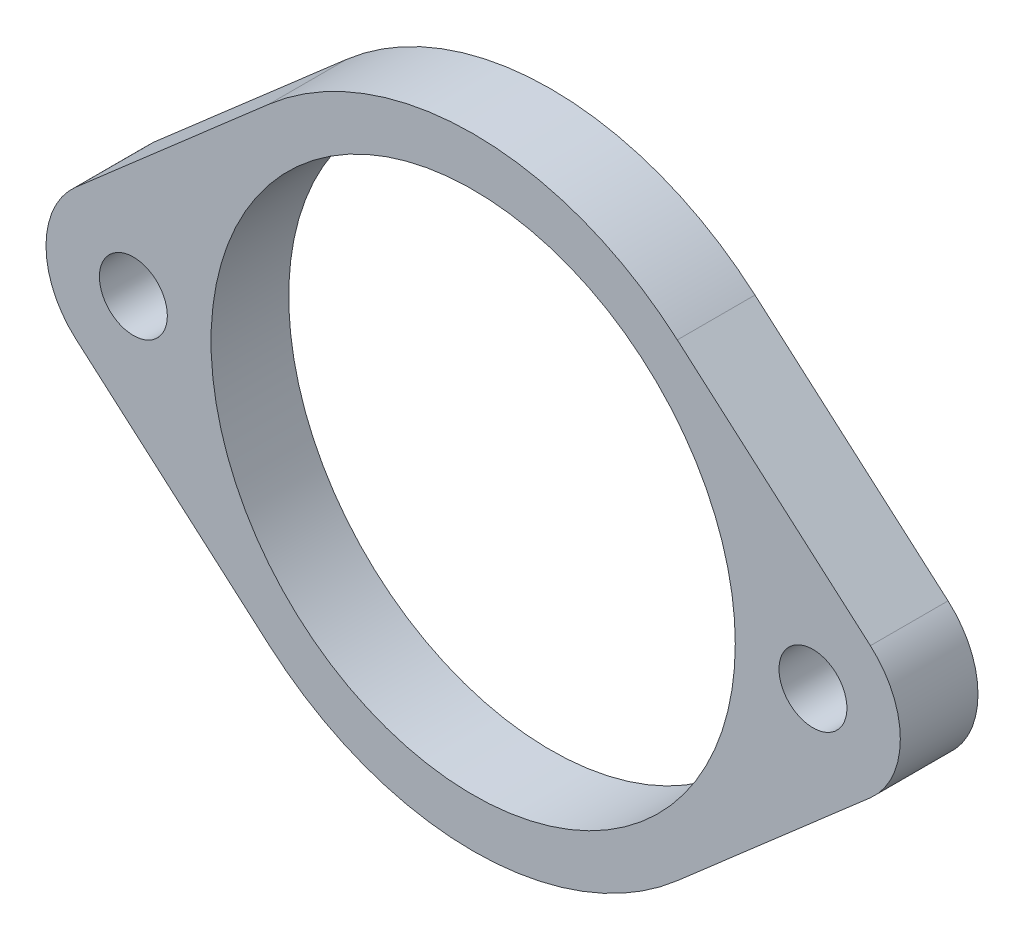
SolidWorks part; units mm, degrees
ref_plane "Front Plane" through (0, 0, 0) normal (0, 0, 1) x (1, 0, 0)
ref_plane "Top Plane" through (0, 0, 0) normal (0, 1, 0) x (1, 0, 0)
ref_plane "Right Plane" through (0, 0, 0) normal (1, 0, 0) x (0, 0, -1)
sketch "Sketch1" plane through (0, 0, 0) normal (0, 0, 1) x (1, 0, 0)
  line L4 (-16.6914, 19.1457) -> (-32.4757, 5.3847)
  line L5 (-32.4757, -5.3847) -> (-16.6914, -19.1457)
  line L6 (16.6914, -19.1457) -> (32.4757, -5.3847)
  line L7 (32.4757, 5.3847) -> (16.6914, 19.1457)
  line L8 (-16.6914, 19.1457) -> (-32.4757, 5.3847)
  line L9 (-32.4757, -5.3847) -> (-16.6914, -19.1457)
  line L10 (16.6914, -19.1457) -> (32.4757, -5.3847)
  line L11 (32.4757, 5.3847) -> (16.6914, 19.1457)
  circle A0 centre (27.7813, 0) radius 2.7781 construction
  circle A1 centre (-27.7813, 0) radius 2.7781 construction
  circle A2 centre (27.7813, 0) radius 2.7781
  circle A3 centre (-27.7813, 0) radius 2.7781
  arc A4 (16.6914, 19.1457) -> (-16.6914, 19.1457) centre (0, 0) ccw
  arc A5 (-32.4757, 5.3847) -> (-32.4757, -5.3847) centre (-27.7813, 0) ccw
  arc A6 (-16.6914, -19.1457) -> (16.6914, -19.1457) centre (0, 0) ccw
  arc A7 (32.4757, -5.3847) -> (32.4757, 5.3847) centre (27.7813, 0) ccw
  arc A8 (16.6914, 19.1457) -> (-16.6914, 19.1457) centre (0, 0) ccw
  arc A9 (-32.4757, 5.3847) -> (-32.4757, -5.3847) centre (-27.7813, 0) ccw
  arc A10 (-16.6914, -19.1457) -> (16.6914, -19.1457) centre (0, 0) ccw
  arc A11 (32.4757, -5.3847) -> (32.4757, 5.3847) centre (27.7813, 0) ccw
  circle A12 centre (0, 0) radius 21.4313 construction
  circle A13 centre (0, 0) radius 21.4313
  dimension "D1" = 0
extrude "Boss-Extrude1" add sketch "Sketch1" along normal blind 6.35
